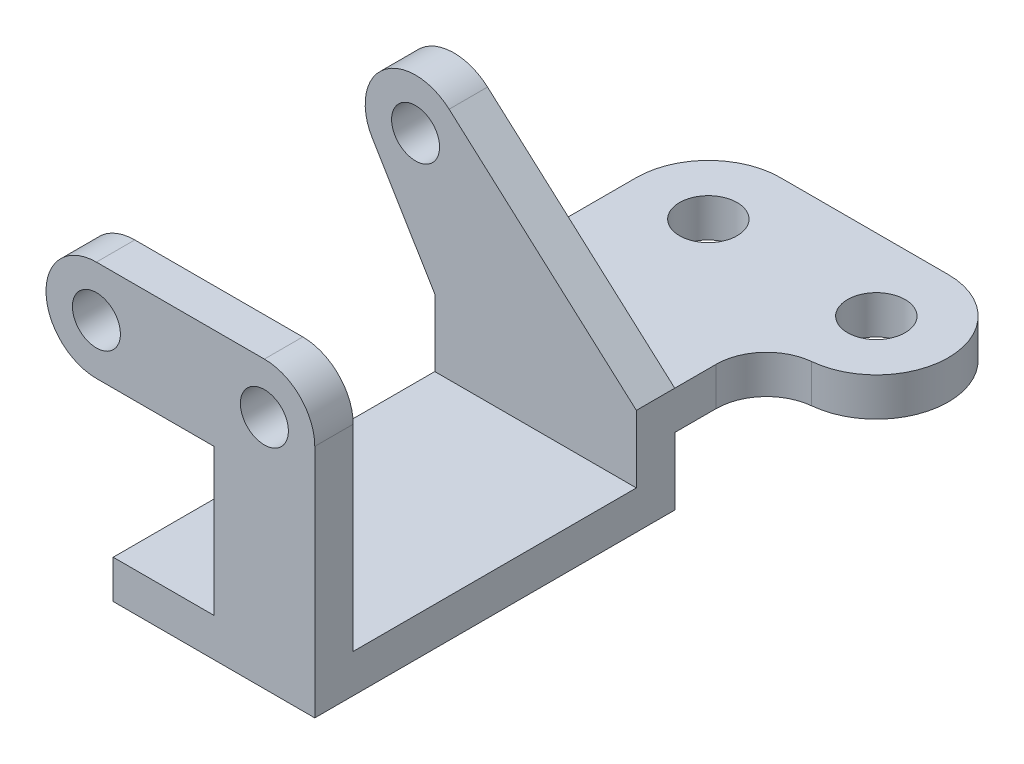
SolidWorks part; units mm, degrees
ref_plane "Front Plane" through (0, 0, 0) normal (0, 0, 1) x (1, 0, 0)
ref_plane "Top Plane" through (0, 0, 0) normal (0, 1, 0) x (1, 0, 0)
ref_plane "Right Plane" through (0, 0, 0) normal (1, 0, 0) x (0, 0, -1)
sketch "Sketch2" plane through (0, 0, 0) normal (1, 0, 0) x (0, 0, -1)
  line L0 (0, 0) -> (-134, 0)
  line L1 (-134, 0) -> (-134, -16)
  line L2 (-134, -16) -> (16, -16)
  line L3 (16, -16) -> (16, 12)
  line L4 (16, 12) -> (84, 12)
  line L5 (84, 12) -> (84, 28)
  line L6 (84, 28) -> (0, 28)
  line L7 (0, 28) -> (0, 0)
  dimension "D1" = 16
  dimension "D2" = 16
  dimension "D3" = 150
  dimension "D4" = 68
  dimension "D5" = 16
  dimension "D6" = 28
extrude "Boss-Extrude1" add sketch "Sketch2" along normal mid plane 84
sketch "Sketch6" plane through (0, 0, 0) normal (0, 0, 1) x (1, 0, 0)
  line L0 (-42, 28) -> (-67.9908, 71.168)
  line L1 (42, 28) -> (-36.0126, 97.6637)
  line L4 (-42, 28) -> (-42, 0)
  line L5 (-42, 0) -> (42, 0)
  line L6 (42, 0) -> (42, 28)
  line L7 (42, 28) -> (-42, 28)
  line L8 (-42, 28) -> (-42, 0)
  line L9 (-42, 0) -> (42, 0)
  line L10 (42, 0) -> (42, 28)
  line L11 (42, 28) -> (-42, 28)
  circle A0 centre (-50, 82) radius 21
  point P8 (0, 0)
  point P9 (0, 0)
  point P10 (0, 0)
  line M11 (42, 28) -> (-42, 28)
  dimension "D2" = 42
  dimension "D3" = 8
  dimension "D4" = 82
  dimension "D1" = 0
extrude "Boss-Extrude3" add sketch "Sketch6" against normal blind 16 contours A0 L0 L1 M11 | A0 L11
sketch "Sketch7" plane through (0, 0, 0) normal (0, 0, 1) x (1, 0, 0)
  line L5 (-42, 28) -> (-42, 0)
  line L6 (-42, 0) -> (42, 0)
  line L7 (42, 0) -> (42, 28)
  line L8 (42, 28) -> (-36.0126, 97.6637)
  line L9 (-67.9908, 71.168) -> (-42, 28)
  line L10 (-42, 28) -> (-42, 0)
  line L11 (-42, 0) -> (42, 0)
  line L12 (42, 0) -> (42, 28)
  line L13 (42, 28) -> (-36.0126, 97.6637)
  line L14 (-67.9908, 71.168) -> (-42, 28)
  circle A0 centre (-50, 82) radius 10
  arc A1 (-36.0126, 97.6637) -> (-67.9908, 71.168) centre (-50, 82) ccw
  arc A2 (-36.0126, 97.6637) -> (-67.9908, 71.168) centre (-50, 82) ccw
  dimension "D2" = 20
  dimension "D1" = 0
extrude "Cut-Extrude2" cut sketch "Sketch7" against normal up to surface (16 mm away) contours A0 up to face at (-28.85, 59.6466, -16)
sketch "Sketch8" plane through (0, 28, 0) normal (0, 1, 0) x (1, 0, 0)
  line L0 (-12, 84) -> (58, 84) construction
  line L1 (-12, 114) -> (58, 114)
  line L2 (-12, 54) -> (58, 54)
  line L4 (-42, 16) -> (42, 16)
  line L5 (42, 16) -> (42, 84)
  line L6 (42, 84) -> (-42, 84)
  line L7 (-42, 84) -> (-42, 16)
  line L8 (-42, 16) -> (42, 16)
  line L9 (42, 16) -> (42, 84)
  line L10 (42, 84) -> (-42, 84)
  line L11 (-42, 84) -> (-42, 16)
  arc A0 (-12, 114) -> (-12, 54) centre (-12, 84) ccw
  arc A1 (58, 54) -> (58, 114) centre (58, 84) ccw
  point P6 (23, 84)
  dimension "D2" = 30
  dimension "D3" = 70
  dimension "D1" = 0
extrude "Boss-Extrude4" add sketch "Sketch8" against normal blind 16
sketch "Sketch9" plane through (0, 28, 0) normal (0, 1, 0) x (1, 0, 0)
  line L5 (42, 16) -> (42, 54)
  line L6 (42, 54) -> (58, 54)
  line L7 (58, 114) -> (-12, 114)
  line L8 (-42, 84) -> (-42, 16)
  line L9 (-42, 16) -> (42, 16)
  line L10 (42, 16) -> (42, 54)
  line L11 (42, 54) -> (58, 54)
  line L12 (58, 114) -> (-12, 114)
  line L13 (-42, 84) -> (-42, 16)
  line L14 (-42, 16) -> (42, 16)
  circle A0 centre (-12, 84) radius 12
  circle A1 centre (58, 84) radius 12
  arc A2 (58, 54) -> (58, 114) centre (58, 84) ccw
  arc A3 (-12, 114) -> (-42, 84) centre (-12, 84) ccw
  arc A4 (58, 54) -> (58, 114) centre (58, 84) ccw
  arc A5 (-12, 114) -> (-42, 84) centre (-12, 84) ccw
  dimension "D2" = 24
  dimension "D1" = 0
extrude "Cut-Extrude3" cut sketch "Sketch9" against normal up to surface (16 mm away) contours A1 | A0 up to face at (18.2553, 12, -65.459)
fillet "Fillet1" radius 21 1 edges at (42, 20, -54)
sketch "Sketch11" plane through (0, 0, 134) normal (0, 0, 1) x (1, 0, 0)
  line L0 (0, 0) -> (0, 61)
  line L1 (-49, 82) -> (21, 82) construction
  line L2 (-49, 103) -> (21, 103)
  line L3 (-49, 61) -> (21, 61)
  line L4 (-42, 0) -> (-42, -16)
  line L5 (-42, -16) -> (42, -16)
  line L6 (42, -16) -> (42, 0)
  line L7 (42, 0) -> (-42, 0)
  line L8 (-42, 0) -> (-42, -16)
  line L9 (-42, -16) -> (42, -16)
  line L10 (42, -16) -> (42, 0)
  line L11 (42, 0) -> (-42, 0)
  line L16 (42, 28) -> (42, 0) construction
  line L17 (42, 82) -> (42, 0)
  arc A0 (-49, 103) -> (-49, 61) centre (-49, 82) ccw
  arc A1 (21, 61) -> (21, 103) centre (21, 82) ccw
  point P8 (-14, 82)
  point P15 (42, 82)
  dimension "D2" = 21
  dimension "D3" = 70
  dimension "D4" = 82
  dimension "D1" = 0
extrude "Boss-Extrude5" add sketch "Sketch11" against normal blind 16
sketch "Sketch12" plane through (0, 0, 134) normal (0, 0, 1) x (1, 0, 0)
  line L7 (-42, 0) -> (-42, -16)
  line L8 (-42, -16) -> (42, -16)
  line L9 (42, -16) -> (42, 82)
  line L10 (21, 103) -> (-49, 103)
  line L11 (-49, 61) -> (0, 61)
  line L12 (0, 61) -> (0, 0)
  line L13 (0, 0) -> (-42, 0)
  line L14 (-42, 0) -> (-42, -16)
  line L15 (-42, -16) -> (42, -16)
  line L16 (42, -16) -> (42, 82)
  line L17 (21, 103) -> (-49, 103)
  line L18 (-49, 61) -> (0, 61)
  line L19 (0, 61) -> (0, 0)
  line L20 (0, 0) -> (-42, 0)
  circle A0 centre (-49, 82) radius 10
  circle A1 centre (21, 82) radius 10
  arc A2 (42, 82) -> (21, 103) centre (21, 82) ccw
  arc A3 (-49, 103) -> (-49, 61) centre (-49, 82) ccw
  arc A4 (42, 82) -> (21, 103) centre (21, 82) ccw
  arc A5 (-49, 103) -> (-49, 61) centre (-49, 82) ccw
  dimension "D2" = 20
  dimension "D1" = 0
extrude "Cut-Extrude5" cut sketch "Sketch12" against normal up to surface (16 mm away) contours A0 | A1 up to face at (-1.3787, 59.1927, 118)
